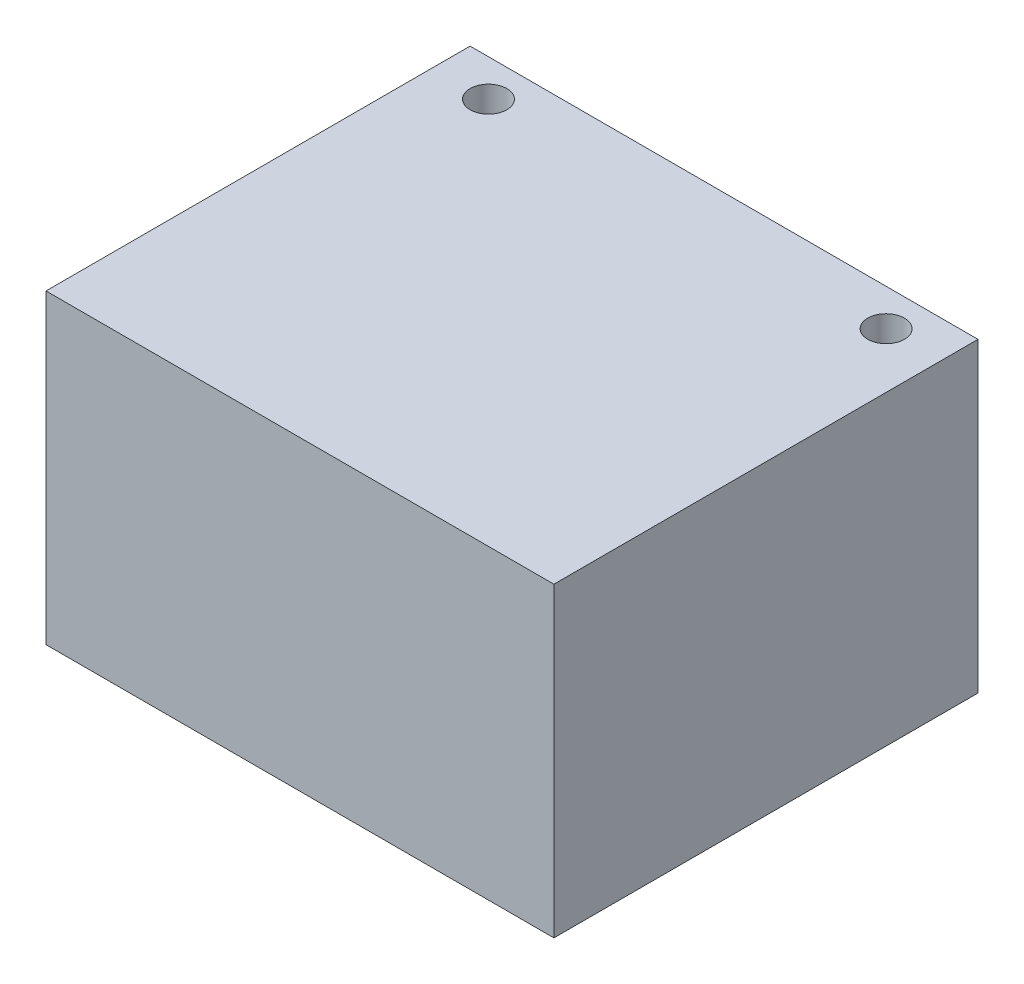
SolidWorks part; units mm, degrees
ref_plane "Front Plane" through (0, 0, 0) normal (0, 0, 1) x (1, 0, 0)
ref_plane "Top Plane" through (0, 0, 0) normal (0, 1, 0) x (1, 0, 0)
ref_plane "Right Plane" through (0, 0, 0) normal (1, 0, 0) x (0, 0, -1)
sketch "Sketch1" plane through (0, 0, 0) normal (0, 1, 0) x (1, 0, 0)
  line L1 (-20.725, -17.305) -> (20.725, -17.305)
  line L2 (-20.725, -17.305) -> (-20.725, 17.305)
  line L3 (-20.725, 17.305) -> (20.725, 17.305)
  line L4 (20.725, -17.305) -> (20.725, 17.305)
  line L5 (-20.725, -17.305) -> (20.725, 17.305) construction
  line L6 (-20.725, 17.305) -> (20.725, -17.305) construction
  point P0 (0, 0)
  dimension "D1" = 41.45
  dimension "D2" = 34.61
extrude "Boss-Extrude1" add sketch "Sketch1" along normal blind 25
sketch "Sketch2" plane through (0, 25, 0) normal (0, 1, 0) x (1, 0, 0)
  line L0 (-20.725, 14.305) -> (20.725, 14.305)
  line L1 (-20.725, 17.305) -> (-20.725, -17.305) construction
  line L2 (20.725, -17.305) -> (20.725, 17.305) construction
  line L3 (20.725, 17.305) -> (-20.725, 17.305) construction
  circle A2 centre (-16.225, 14.305) radius 1.5
  circle A3 centre (16.225, 14.305) radius 1.5
  dimension "D2" = 4.5
  dimension "D3" = 4.5
  dimension "D4" = 3
  dimension "D5" = 3
  dimension "D1" = 3
extrude "Cut-Extrude1" cut sketch "Sketch2" against normal blind 25 contours A2 | A3
